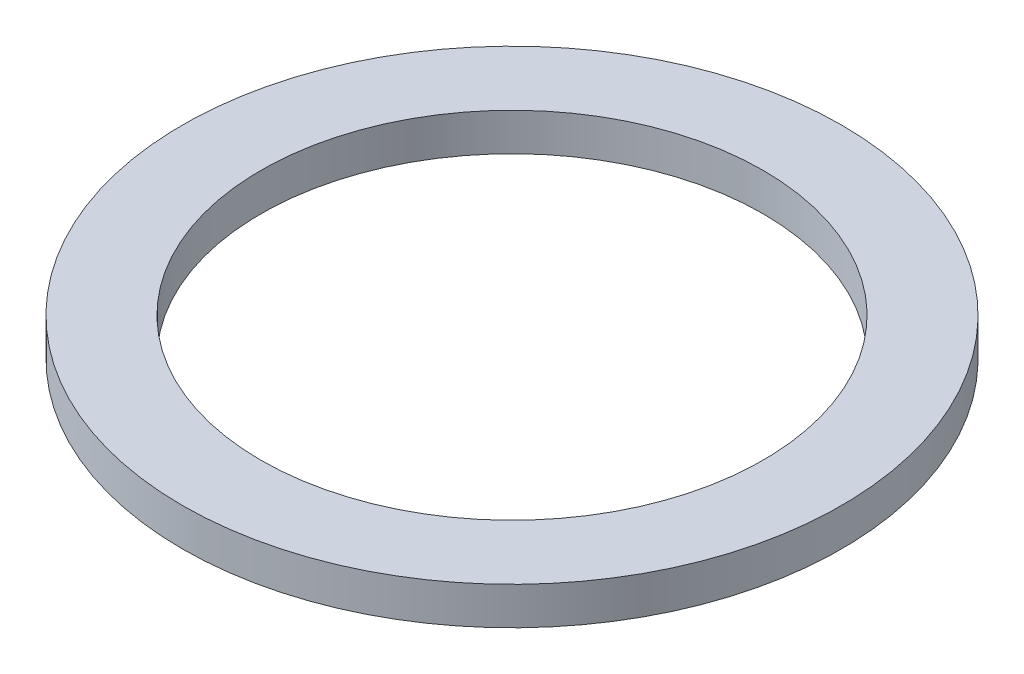
SolidWorks part; units mm, degrees
material "AISI 304"
ref_plane "前视基准面" through (0, 0, 0) normal (0, 0, 1) x (1, 0, 0)
ref_plane "上视基准面" through (0, 0, 0) normal (0, 1, 0) x (1, 0, 0)
ref_plane "右视基准面" through (0, 0, 0) normal (1, 0, 0) x (0, 0, -1)
other "Configuration Table"
sketch "草图1" plane through (0, 0, 0) normal (0, 1, 0) x (1, 0, 0)
  circle A0 centre (0, 0) radius 40
  circle A1 centre (0, 0) radius 52.5
  dimension "D1" = 80
  dimension "D2" = 105
extrude "凸台-拉伸1" add sketch "草图1" along normal blind 6
